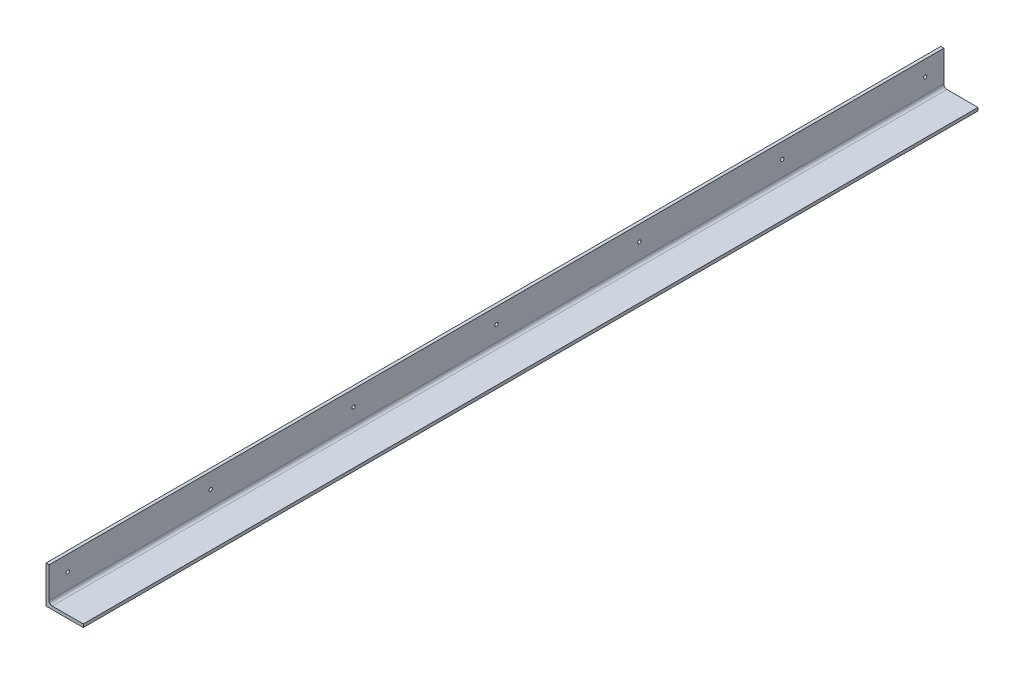
SolidWorks part; units mm, degrees
material "1060 Alloy"
ref_plane "Front Plane" through (0, 0, 0) normal (0, 0, 1) x (1, 0, 0)
ref_plane "Top Plane" through (0, 0, 0) normal (0, 1, 0) x (1, 0, 0)
ref_plane "Right Plane" through (0, 0, 0) normal (1, 0, 0) x (0, 0, -1)
sketch "Sketch1" plane through (0, 0, 0) normal (0, 0, 1) x (1, 0, 0)
  line L0 (0, 0) -> (0, 76.2)
  line L1 (0, 76.2) -> (6.35, 76.2)
  line L2 (6.35, 76.2) -> (6.35, 12.7)
  line L3 (12.7, 6.35) -> (76.2, 6.35)
  line L4 (76.2, 6.35) -> (76.2, 0)
  line L5 (76.2, 0) -> (0, 0)
  arc A0 (6.35, 12.7) -> (12.7, 6.35) centre (12.7, 12.7) ccw
  dimension "D3" = 6.35
  dimension "D1" = 6.35
  dimension "D2" = 76.2
extrude "Boss-Extrude1" add sketch "Sketch1" along normal blind 1828.8
sketch "Sketch2" plane through (6.35, 0, 0) normal (1, 0, 0) x (0, 0, -1)
  line L0 (-1828.8, 12.7) -> (-1828.8, 76.2) construction
  line L1 (-1828.8, 76.2) -> (0, 76.2) construction
  point P0 (-1790.7, 44.45)
  point P5 (-1498.6, 44.45)
  point P7 (-1206.5, 44.45)
  point P8 (-914.4, 44.45)
  point P9 (-622.3, 44.45)
  point P10 (-330.2, 44.45)
  point P11 (-38.1, 44.45)
  dimension "D1" = 38.1
  dimension "D2" = 31.75
  dimension "D4" = 292.1
  dimension "D3" = 7
hole_wizard "Ø0.25 (6.74688) Diameter Hole1" positions "Sketch3" profile "Sketch4" hole size "Ø0.25" standard "ANSI Metric" end condition through all
sketch "Sketch3" plane through (6.35, 0, 0) normal (1, 0, 0) x (0, 0, -1)
  point P0 (-1790.7, 44.45)
  point P3 (-1498.6, 44.45)
  point P6 (-1206.5, 44.45)
  point P9 (-914.4, 44.45)
  point P12 (-622.3, 44.45)
  point P15 (-330.2, 44.45)
  point P18 (-38.1, 44.45)
sketch "Sketch4" plane through (6.35, 44.45, 1790.7) normal (0, 1, 0) x (0, 0, -1)
  line L0 (0, 0) -> (0, 6.35)
  line L1 (0, 6.35) -> (3.3734, 6.35)
  line L2 (3.3734, 6.35) -> (3.3734, 0)
  line L5 (3.3734, 0) -> (0, 0)
  line L11 (0, -6.35) -> (0, 107.95) construction
  dimension "Thru Hole Dia." = 6.7469
  dimension "Thru Hole Depth" = 6.35
